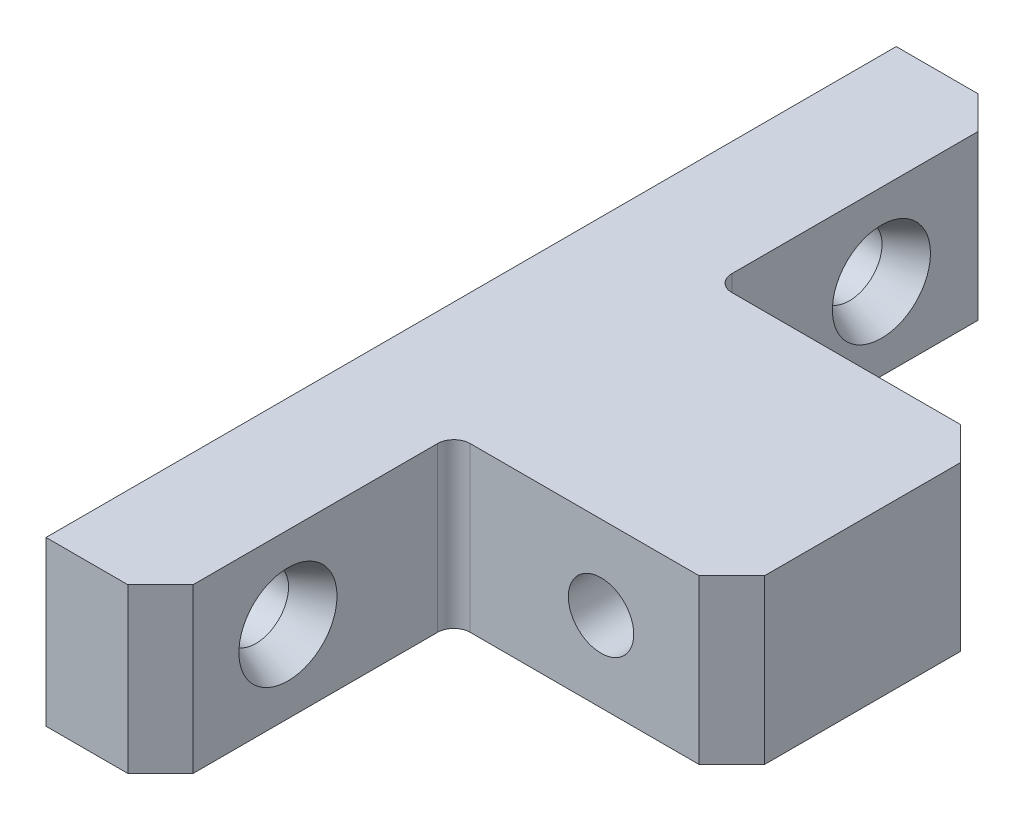
SolidWorks part; units mm, degrees
ref_plane "Спереди" through (0, 0, 0) normal (0, 0, 1) x (1, 0, 0)
ref_plane "Сверху" through (0, 0, 0) normal (0, 1, 0) x (1, 0, 0)
ref_plane "Справа" through (0, 0, 0) normal (1, 0, 0) x (0, 0, -1)
sketch "Эскиз1" plane through (0, 0, 0) normal (1, 0, 0) x (0, 0, -1)
  line L0 (0, 6.8534) -> (0, 3.666) construction
  line L3 (-26, 5.1038) -> (26, 5.1038)
  line L4 (-26, 5.1038) -> (-26, -4.8962)
  line L5 (-26, -4.8962) -> (26, -4.8962)
  line L6 (26, 5.1038) -> (26, -4.8962)
  dimension "D1" = 26
  dimension "D2" = 26
extrude "Вытянуть1" add sketch "Эскиз1" along normal blind 24
sketch "Эскиз2" plane through (24, 0, 0) normal (1, 0, 0) x (0, 0, -1)
  line L0 (-0.0551, -4.8962) -> (-0.0551, -16.5579) construction
  line L3 (-8.0551, 5.7643) -> (-31.6256, 5.7643)
  line L4 (-8.0551, 5.7643) -> (-8.0551, -8.5217)
  line L5 (-8.0551, -8.5217) -> (-31.6256, -8.5217)
  line L6 (-31.6256, 5.7643) -> (-31.6256, -8.5217)
  line L7 (31.5154, 5.7643) -> (31.5154, -8.5217)
  line L8 (7.9449, -8.5217) -> (31.5154, -8.5217)
  line L9 (7.9449, 5.7643) -> (7.9449, -8.5217)
  line L10 (7.9449, 5.7643) -> (31.5154, 5.7643)
  dimension "D1" = 8
extrude "Вырез-Вытянуть1" cut sketch "Эскиз2" against normal blind 17
fillet "Скругление1" radius 1 2 edges at (7, 0.1038, -7.9449) (7, 0.1038, 8.0551)
chamfer "Фаска1" distance 2 angle 45 4 edges at (24, 0.1038, -7.9449) (24, 0.1038, 8.0551) (7, 0.1038, -26) (7, 0.1038, 26)
sketch "Эскиз3" plane through (7, 0, 0) normal (1, 0, 0) x (0, 0, -1)
  line L0 (-0.0551, -4.8962) -> (-0.0551, -7.2502) construction
  line L1 (-26, 0.1038) -> (-33.8166, 0.1038) construction
  line L4 (-18.2027, 2.1753) -> (-18.2027, 9.8978) construction
  circle A0 centre (-18.2027, 0.1038) radius 2
  circle A1 centre (18.0924, 0.1038) radius 2
extrude "Вырез-Вытянуть2" cut sketch "Эскиз3" against normal through all
sketch "Эскиз4" plane through (0, 0, 8.0551) normal (0, 0, 1) x (1, 0, 0)
  line L1 (23, 0) -> (34.7489, 0) construction
  circle A0 centre (16, 0) radius 2
extrude "Вырез-Вытянуть3" cut sketch "Эскиз4" against normal through all
sketch "Эскиз5" plane through (7, 0, 0) normal (1, 0, 0) x (0, 0, -1)
  circle A0 centre (-18.2027, 0.1038) radius 3
  circle A1 centre (18.0924, 0.1038) radius 3
extrude "Вырез-Вытянуть4" cut sketch "Эскиз5" against normal blind 2 draft 27
sketch "Эскиз6" plane through (0, 0, 0) normal (-1, 0, 0) x (0, 0, 1)
  line L0 (0.0551, 2.1753) -> (0.0551, 8.4187) construction
  line L1 (-26, 0.1038) -> (-40.9889, 0.1038) construction
  circle A0 centre (0, 0) radius 2
extrude "Вытянуть2" cut sketch "Эскиз6" against normal blind 10
